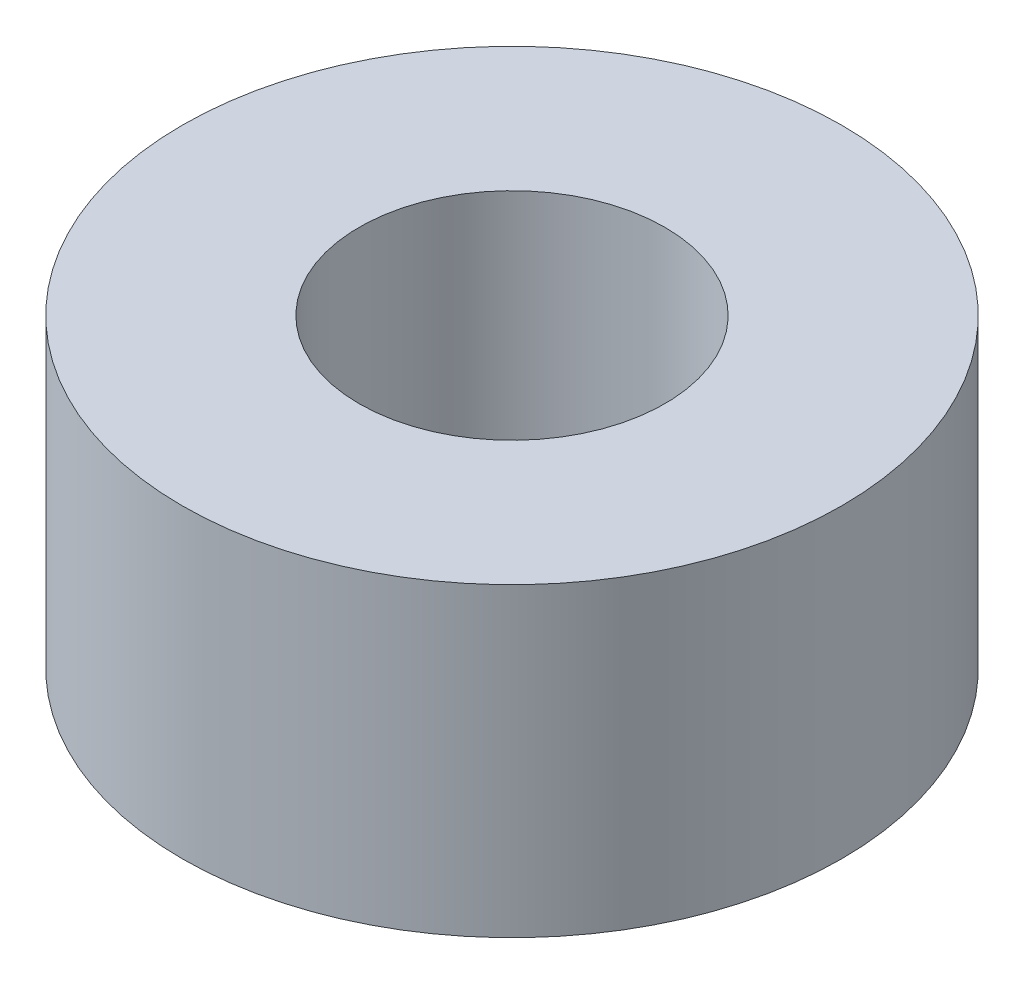
SolidWorks part; units mm, degrees
material "Nylon 6/10"
ref_plane "Front Plane" through (0, 0, 0) normal (0, 0, 1) x (1, 0, 0)
ref_plane "Top Plane" through (0, 0, 0) normal (0, 1, 0) x (1, 0, 0)
ref_plane "Right Plane" through (0, 0, 0) normal (1, 0, 0) x (0, 0, -1)
sketch "Sketch1" plane through (0, 0, 0) normal (0, 1, 0) x (1, 0, 0)
  circle A0 centre (0, 0) radius 5.5
  circle A1 centre (0, 0) radius 2.55
extrude "Boss-Extrude1" add sketch "Sketch1" along normal blind 5.1
